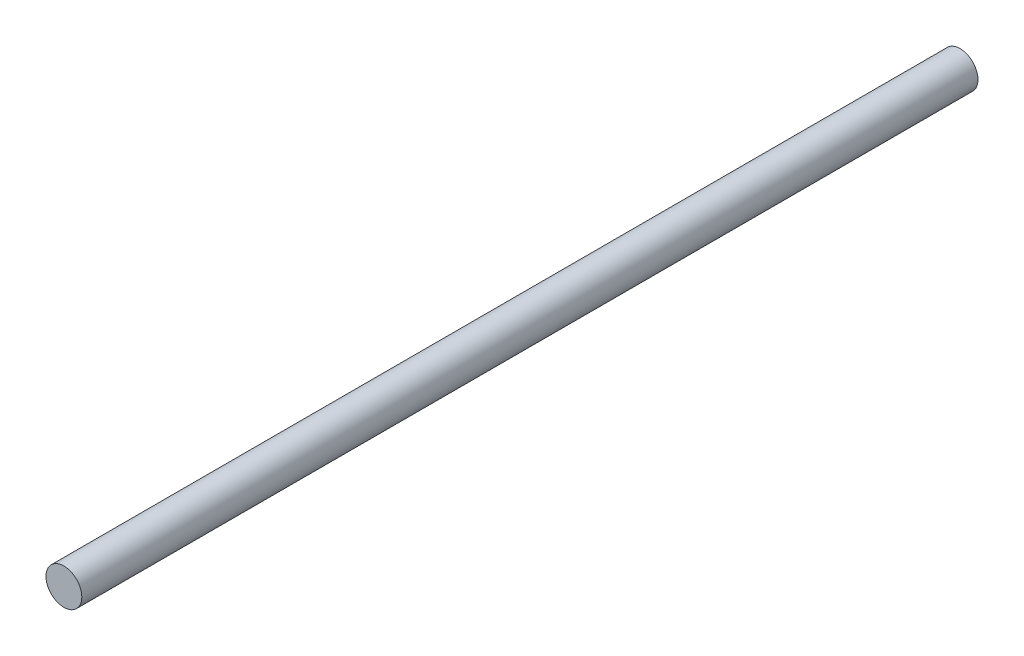
SolidWorks part; units mm, degrees
ref_plane "Plan de face" through (0, 0, 0) normal (0, 0, 1) x (1, 0, 0)
ref_plane "Plan de dessus" through (0, 0, 0) normal (0, 1, 0) x (1, 0, 0)
ref_plane "Plan de droite" through (0, 0, 0) normal (1, 0, 0) x (0, 0, -1)
sketch "Esquisse1" plane through (0, 0, 0) normal (0, 0, 1) x (1, 0, 0)
  circle A0 centre (0, 0) radius 10
  dimension "D1" = 20
extrude "Boss.-Extru.1" add sketch "Esquisse1" along normal blind 500
